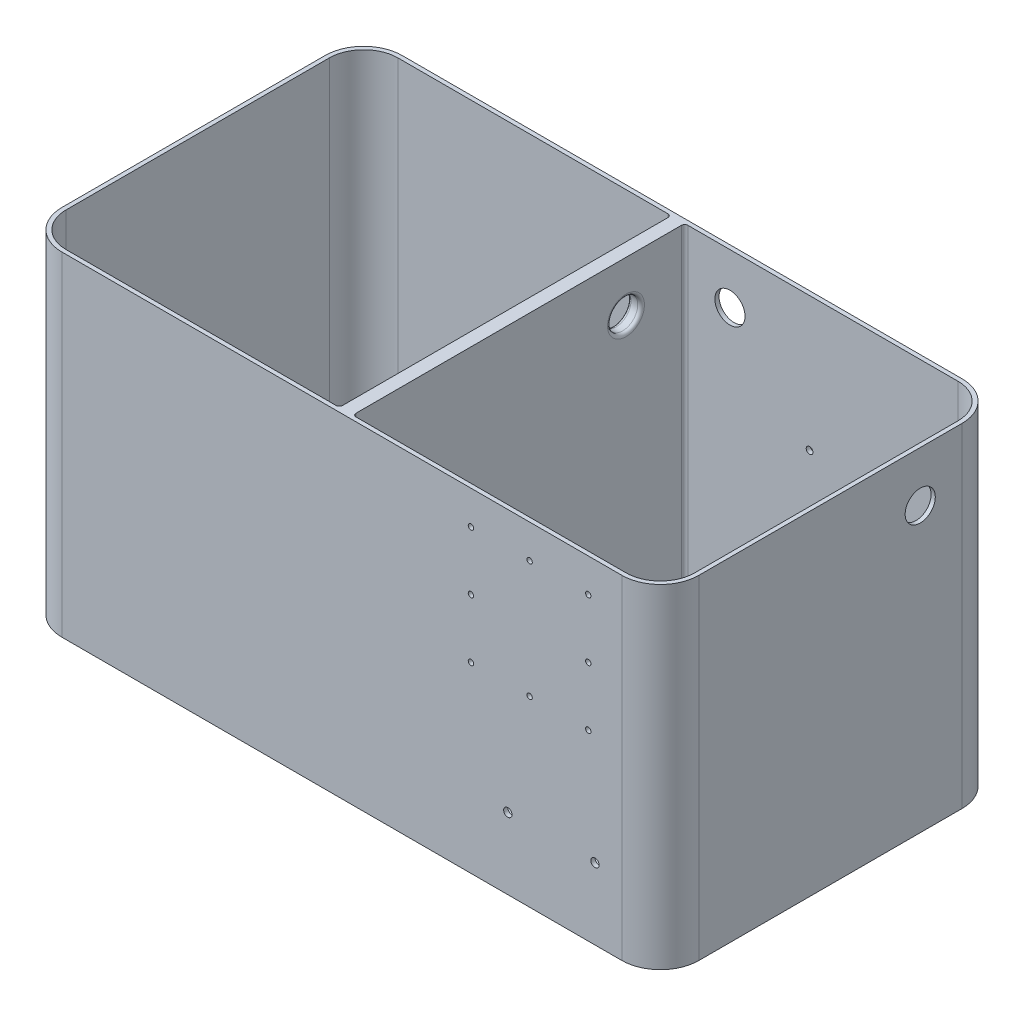
SolidWorks part; units mm, degrees
ref_plane "前视基准面" through (0, 0, 0) normal (0, 0, 1) x (1, 0, 0)
ref_plane "上视基准面" through (0, 0, 0) normal (0, 1, 0) x (1, 0, 0)
ref_plane "右视基准面" through (0, 0, 0) normal (1, 0, 0) x (0, 0, -1)
other "Configuration Table"
sketch "草图1" plane through (0, 0, 0) normal (0, 1, 0) x (1, 0, 0)
  line L1 (-167, 101.5) -> (167, 101.5)
  line L2 (-190, 78.5) -> (-190, -78.5)
  line L3 (-167, -101.5) -> (167, -101.5)
  line L4 (190, 78.5) -> (190, -78.5)
  line L5 (-190, 101.5) -> (190, -101.5) construction
  line L6 (-190, -101.5) -> (190, 101.5) construction
  arc A0 (167, -101.5) -> (190, -78.5) centre (167, -78.5) ccw
  arc A1 (167, 101.5) -> (190, 78.5) centre (167, 78.5) cw
  arc A2 (-190, -78.5) -> (-167, -101.5) centre (-167, -78.5) ccw
  arc A3 (-167, 101.5) -> (-190, 78.5) centre (-167, 78.5) ccw
  point P0 (0, 0)
  dimension "D3" = 23
  dimension "D1" = 380
  dimension "D2" = 203
extrude "凸台-拉伸1" add sketch "草图1" along normal blind 199
sketch "草图3" plane through (0, 199, 0) normal (0, 1, 0) x (1, 0, 0)
  line L0 (-190, 78.5) -> (-190, -78.5) construction
  line L1 (-167, 99) -> (167, 99)
  line L2 (-187.5, 78.5) -> (-187.5, -78.5)
  line L3 (-167, -99) -> (167, -99)
  line L4 (187.5, 78.5) -> (187.5, -78.5)
  line L5 (-187.5, 99) -> (187.5, -99) construction
  line L6 (-187.5, -99) -> (187.5, 99) construction
  line L7 (190, -78.5) -> (190, 78.5) construction
  arc A0 (-187.5, -78.5) -> (-167, -99) centre (-167, -78.5) ccw
  arc A1 (167, -99) -> (187.5, -78.5) centre (167, -78.5) ccw
  arc A2 (167, 99) -> (187.5, 78.5) centre (167, 78.5) cw
  arc A3 (-167, 99) -> (-187.5, 78.5) centre (-167, 78.5) ccw
  point P0 (0, 0)
  dimension "D5" = 20.5
  dimension "D1" = 198
  dimension "D2" = 375
  dimension "D3" = 2.5
  dimension "D4" = 2.5
extrude "切除-拉伸1" cut sketch "草图3" against normal blind 195
sketch "草图4" plane through (0, 4, 0) normal (0, 1, 0) x (1, 0, 0)
  line L0 (0, 99) -> (0, -99) construction
  line L1 (167, 99) -> (-167, 99) construction
  line L2 (-167, -99) -> (167, -99) construction
  line L3 (-4, 99) -> (-4, -99)
  line L4 (-167, -99) -> (167, -99) construction
  line L5 (4, 99) -> (4, -99)
  line L6 (-4, 99) -> (4, 99)
  line L7 (-4, -99) -> (4, -99)
  dimension "D1" = 4
extrude "凸台-拉伸2" add sketch "草图4" along normal blind 195
fillet "圆角1" radius 2 16 edges at (85.5, 4, 99) (181.4957, 4, 92.9957) (187.5, 4, 0) (181.4957, 4, -92.9957) (-85.5, 4, 99) (-181.4957, 4, 92.9957) (-187.5, 4, 0) (-181.4957, 4, -92.9957) (-4, 101.5, -99) (-4, 4, 0) (-4, 101.5, 99) (4, 101.5, 99) (4, 101.5, -99) (4, 4, 0) (85.5, 4, -99) (-85.5, 4, -99)
sketch "草图6" plane through (0, 0, -101.5) normal (0, 0, -1) x (-1, 0, 0)
  line L0 (0, 199) -> (0, 0) construction
  line L1 (-167, 199) -> (167, 199) construction
  line L2 (-6, 199) -> (-6, 0) construction
  line L4 (-167, 0) -> (167, 0) construction
  line L5 (6, 199) -> (6, 0) construction
  line L6 (-167, 199) -> (-167, 0) construction
  circle A0 centre (-155, 119) radius 2
  circle A1 centre (-155, 64) radius 2
  circle A2 centre (-78.5, 64) radius 2
  circle A3 centre (-78.5, 119) radius 2
  circle A4 centre (-31, 169) radius 9
  point P13 (-155, 119)
  point P14 (-155, 64)
  point P17 (-78.5, 119)
  point P18 (-78.5, 64)
  dimension "D5" = 4
  dimension "D6" = 4
  dimension "D7" = 4
  dimension "D8" = 4
  dimension "D10" = 18
  dimension "D1" = 12
  dimension "D2" = 12
  dimension "D3" = 76.5
  dimension "D4" = 55
  dimension "D9" = 80
  dimension "D11" = 25
  dimension "D12" = 30
extrude "切除-拉伸2" cut sketch "草图6" against normal up to next contours A2 | A3 | A0 | A1 | A4
sketch "草图7" plane through (4, 0, 0) normal (1, 0, 0) x (0, 0, -1)
  line L0 (99, 199) -> (99, 0) construction
  line L1 (78.5, 0) -> (101.5, 0) construction
  line L2 (-78.5, 199) -> (78.5, 199) construction
  circle A0 centre (64, 169) radius 9
  dimension "D2" = 18
  dimension "D1" = 35
  dimension "D3" = 30
extrude "切除-拉伸3" cut sketch "草图7" against normal up to next
fillet "圆角2" radius 2 2 edges at (-4, 169, -73) (4, 169, -73)
sketch "草图9" plane through (190, 0, 0) normal (1, 0, 0) x (0, 0, -1)
  line L0 (-78.5, 199) -> (78.5, 199) construction
  line L1 (78.5, 199) -> (78.5, 0) construction
  circle A0 centre (53.5, 169) radius 9
  dimension "D1" = 18
  dimension "D2" = 30
  dimension "D3" = 25
extrude "切除-拉伸4" cut sketch "草图9" against normal up to next
sketch "草图11" plane through (0, 0, 101.5) normal (0, 0, 1) x (1, 0, 0)
  line L0 (167, 199) -> (167, 0) construction
  line L1 (77, 179) -> (147, 179) construction
  line L2 (77, 179) -> (77, 109) construction
  line L3 (77, 109) -> (147, 109) construction
  line L4 (147, 179) -> (147, 109) construction
  line L5 (77, 179) -> (147, 109) construction
  line L6 (77, 109) -> (147, 179) construction
  line L7 (-167, 199) -> (167, 199) construction
  circle A0 centre (77, 179) radius 1.6
  circle A1 centre (147, 179) radius 1.6
  circle A2 centre (77, 109) radius 1.6
  circle A3 centre (147, 109) radius 1.6
  point P0 (112, 144)
  dimension "D5" = 3.2
  dimension "D6" = 3.2
  dimension "D7" = 3.2
  dimension "D8" = 3.2
  dimension "D1" = 70
  dimension "D2" = 70
  dimension "D3" = 20
  dimension "D4" = 20
extrude "切除-拉伸5" cut sketch "草图11" against normal up to next
sketch "草图12" plane through (0, 0, 101.5) normal (0, 0, 1) x (1, 0, 0)
  line L0 (77, 179) -> (147, 109) construction
  line L1 (77, 179) -> (147, 179) construction
  line L2 (77, 179) -> (77, 109) construction
  line L3 (77, 109) -> (147, 109) construction
  line L4 (147, 179) -> (147, 109) construction
  line L5 (77, 109) -> (147, 179) construction
  circle A1 centre (77, 144) radius 1.6
  circle A2 centre (112, 179) radius 1.6
  circle A3 centre (147, 144) radius 1.6
  circle A4 centre (112, 109) radius 1.6
  point P2 (112, 144)
  point P17 (112, 144)
  dimension "D2" = 3.2
  dimension "D1" = 35
  dimension "D4" = 70
  dimension "D5" = 70
  dimension "D3" = 4
extrude "切除-拉伸6" cut sketch "草图12" against normal up to next
sketch "草图13" plane through (0, 0, 101.5) normal (0, 0, 1) x (1, 0, 0)
  line L0 (125, 71) -> (125, 14) construction
  line L5 (93, 71) -> (157, 71) construction
  line L6 (93, 71) -> (93, 14) construction
  line L7 (93, 14) -> (157, 14) construction
  line L8 (157, 71) -> (157, 14) construction
  line L9 (93, 42.5) -> (157, 42.5) construction
  line L10 (167, 199) -> (167, 0) construction
  line L11 (-167, 0) -> (167, 0) construction
  circle A0 centre (99, 42.5) radius 2.5
  circle A1 centre (151, 42.5) radius 2.5
  dimension "D3" = 5
  dimension "D1" = 64
  dimension "D2" = 57
  dimension "D4" = 26
  dimension "D6" = 52
  dimension "D7" = 10
  dimension "D8" = 14
  dimension "D5" = 2
extrude "切除-拉伸7" cut sketch "草图13" against normal up to next
equation "\"D4@草图13\"=52/2MM"
